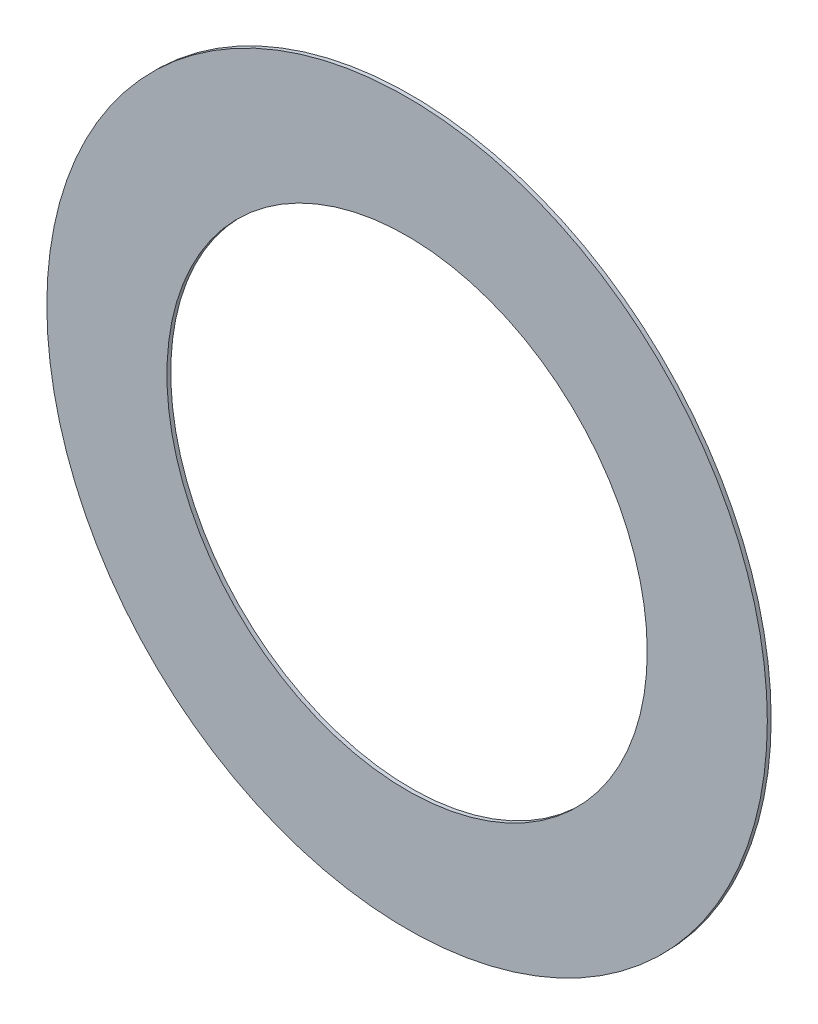
SolidWorks part; units mm, degrees
ref_plane "Front Plane" through (0, 0, 0) normal (0, 0, 1) x (1, 0, 0)
ref_plane "Top Plane" through (0, 0, 0) normal (0, 1, 0) x (1, 0, 0)
ref_plane "Right Plane" through (0, 0, 0) normal (1, 0, 0) x (0, 0, -1)
sketch "Sketch1" plane through (0, 0, 0) normal (0, 0, 1) x (1, 0, 0)
  line L0 (-2.3812, 0) -> (2.3812, 0) construction
  line L1 (0, -2.3812) -> (0, 2.3812) construction
  circle A0 centre (0, 0) radius 2.3812
  circle A1 centre (0, 0) radius 1.5875
  point P4 (0, 0)
  point P9 (0, 0)
  dimension "ID" = 3.175
  dimension "OD" = 4.7625
sketch "Sketch2" plane through (0, 0, 0) normal (1, 0, 0) x (0, 0, -1)
  line L0 (0.0127, 2.3812) -> (-0.0127, 2.3812) construction
  line L1 (0, 2.3812) -> (0, -2.3812) construction
  point P4 (0, 2.3812)
  dimension "Thickness" = 0.0254
sketch "Sketch3" plane through (0, 0, 0) normal (0, 0, 1) x (1, 0, 0)
  line L0 (0, -2.3812) -> (0, 2.3812) construction
  circle A0 centre (0, 0) radius 2.3812
  circle A1 centre (0, 0) radius 1.5875
  circle A2 centre (0, 0) radius 1.5875 construction
extrude "Boss-Extrude1" add sketch "Sketch3" along normal mid plane 0.0254
equation "\"D1@Boss-Extrude1\" = \"Thickness@Sketch2\""
